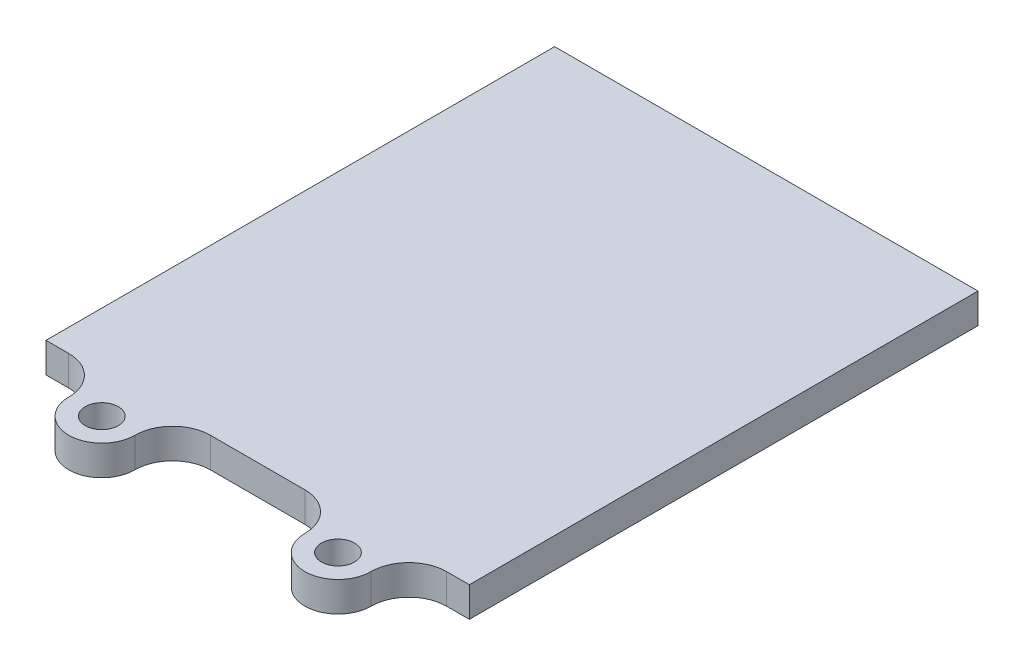
SolidWorks part; units mm, degrees
material "Acrylic (Medium-high impact)"
ref_plane "Front Plane" through (0, 0, 0) normal (0, 0, 1) x (1, 0, 0)
ref_plane "Top Plane" through (0, 0, 0) normal (0, 1, 0) x (1, 0, 0)
ref_plane "Right Plane" through (0, 0, 0) normal (1, 0, 0) x (0, 0, -1)
sketch "Sketch1" plane through (0, 0, 0) normal (0, 1, 0) x (1, 0, 0)
  line L1 (-43.815, -47.5) -> (43.815, -47.5) construction
  line L2 (-43.815, -47.5) -> (-43.815, 47.5) construction
  line L3 (-43.815, 47.5) -> (43.815, 47.5) construction
  line L4 (43.815, -47.5) -> (43.815, 47.5) construction
  line L5 (-43.815, -47.5) -> (43.815, 47.5) construction
  line L6 (-43.815, 47.5) -> (43.815, -47.5) construction
  line L8 (44.815, -53.85) -> (-44.815, -53.85)
  line L9 (44.815, -53.85) -> (44.815, 53.85)
  line L10 (44.815, 53.85) -> (-44.815, 53.85)
  line L11 (-44.815, -53.85) -> (-44.815, 53.85)
  line L12 (44.815, -53.85) -> (-44.815, 53.85) construction
  line L13 (44.815, 53.85) -> (-44.815, -53.85) construction
  point P0 (0, 0)
  point P6 (0, 0)
  dimension "D1" = 95
  dimension "D2" = 87.63
  dimension "D3" = 6.35
  dimension "D4" = 1
extrude "Boss-Extrude1" add sketch "Sketch1" along normal blind 6.35
sketch "Sketch2" plane through (0, 0, 0) normal (0, 1, 0) x (1, 0, 0)
  line L1 (-32, -61.85) -> (-32, -53.85) construction
  line L2 (-40, -53.85) -> (-10, -53.85)
  line L3 (-44.815, -53.85) -> (44.815, -53.85) construction
  line L4 (0, -53.85) -> (0, -79.0625) construction
  line L5 (40, -53.85) -> (10, -53.85)
  line L6 (32, -61.85) -> (32, -53.85) construction
  circle A5 centre (-25, -61.85) radius 3.5
  circle A6 centre (-25, -61.85) radius 7 construction
  arc A7 (-40, -53.85) -> (-32, -61.85) centre (-40, -61.85) cw
  arc A8 (-32, -61.85) -> (-18, -61.85) centre (-25, -61.85) ccw
  arc A9 (-10, -53.85) -> (-18, -61.85) centre (-10, -61.85) ccw
  arc A10 (10, -53.85) -> (18, -61.85) centre (10, -61.85) cw
  circle A11 centre (25, -61.85) radius 7 construction
  arc A12 (32, -61.85) -> (18, -61.85) centre (25, -61.85) cw
  arc A13 (40, -53.85) -> (32, -61.85) centre (40, -61.85) ccw
  circle A14 centre (25, -61.85) radius 3.5
  dimension "D1" = 7
  dimension "D3" = 8
  dimension "D2" = 14
  dimension "D4" = 50
extrude "Boss-Extrude2" add sketch "Sketch2" along normal blind 6.35 contours A5 | A13 L5 A10 A12 A14 | A9 A8 A7 L2
